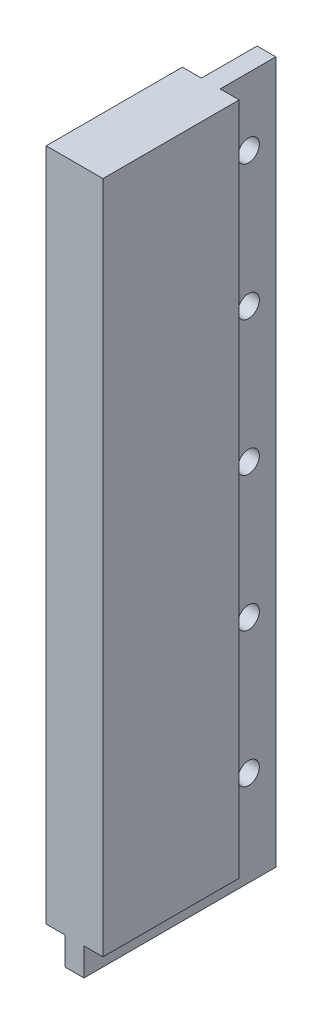
SolidWorks part; units mm, degrees
ref_plane "Front Plane" through (0, 0, 0) normal (1, 0, 0) x (0, 1, 0)
ref_plane "Top Plane" through (0, 0, 0) normal (0, 0, 1) x (0, 1, 0)
ref_plane "Right Plane" through (0, 0, 0) normal (0, 1, 0) x (-1, 0, 0)
sketch "Sketch1" plane through (0, 0, 0) normal (1, 0, 0) x (0, 1, 0)
  line L1 (0, 0) -> (118.75, 0)
  line L2 (0, 0) -> (0, 24)
  line L3 (0, 24) -> (118.75, 24)
  line L4 (118.75, 0) -> (118.75, 24)
  dimension "D1" = 118.75
  dimension "D2" = 24
extrude "Boss-Extrude1" add sketch "Sketch1" against normal blind 10
sketch "Sketch2" plane through (0, 0, 0) normal (0, -1, 0) x (1, 0, 0)
  line L1 (-10, 0) -> (-6.65, 0)
  line L2 (-10, 0) -> (-10, -9.8)
  line L3 (-10, -9.8) -> (-6.65, -9.8)
  line L4 (-6.65, 0) -> (-6.65, -9.8)
  line L5 (0, 0) -> (-3.35, 0)
  line L6 (0, 0) -> (0, -9.8)
  line L7 (0, -9.8) -> (-3.35, -9.8)
  line L8 (-3.35, 0) -> (-3.35, -9.8)
  line L9 (-6.65, -9.8) -> (-3.35, -9.8)
  line L10 (-6.65, -9.8) -> (-6.65, 0)
  line L11 (-6.65, 0) -> (-3.35, 0)
  line L12 (-3.35, -9.8) -> (-3.35, 0)
  line M12 (-10, 0) -> (0, 0)
  dimension "D1" = 9.8
  dimension "D2" = 3.35
  dimension "D3" = 3.35
extrude "Boss-Extrude2" add sketch "Sketch2" against normal through all contours L4 L9 L8 M12
sketch "Sketch3" plane through (0, 0, 0) normal (0, -1, 0) x (1, 0, 0)
  line L0 (-3.35, 20.65) -> (-3.35, 3.35)
  line L1 (0, 24) -> (-10, 24)
  line L2 (0, 24) -> (0, 0)
  line L3 (0, 0) -> (-10, 0)
  line L4 (-10, 24) -> (-10, 0)
  line L5 (-3.35, 3.35) -> (-6.65, 3.35)
  line L6 (-6.65, 20.65) -> (-6.65, 3.35)
  line L7 (-3.35, 20.65) -> (-6.65, 20.65)
  line L9 (-6.65, 20.65) -> (-3.35, 20.65)
  line L10 (-6.65, 20.65) -> (-6.65, 24)
  line L11 (-6.65, 24) -> (-3.35, 24)
  line L12 (-3.35, 20.65) -> (-3.35, 24)
  line L13 (-6.65, 3.35) -> (-3.35, 3.35)
  line L14 (-6.65, 3.35) -> (-6.65, -9.8)
  line L15 (-6.65, -9.8) -> (-3.35, -9.8)
  line L16 (-3.35, 3.35) -> (-3.35, -9.8)
  line M13 (-6.65, 0) -> (-6.65, -9.8)
  line M14 (-6.65, -9.8) -> (-3.35, -9.8)
  line M15 (-3.35, -9.8) -> (-3.35, 0)
  dimension "D1" = 3.35
extrude "Boss-Extrude3" add sketch "Sketch3" along normal blind 4.9 contours L7 L12 L1 L10 | L0 L7 L6 L5 | L16 L5 L14 L3 | L3 M15 M13 M14
sketch "Sketch4" plane through (-6.65, 0, 0) normal (-1, 0, 0) x (0, -1, 0)
  line L1 (-106.875, 0) -> (-118.75, 0)
  line L2 (-106.875, 0) -> (-106.875, -5)
  line L3 (-106.875, -5) -> (-118.75, -5)
  line L4 (-118.75, 0) -> (-118.75, -5)
  circle A0 centre (-106.875, -5) radius 1.9
  dimension "D2" = 3.8
  dimension "D1" = 5
  dimension "D3" = 11.875
extrude "Cut-Extrude1" cut sketch "Sketch4" against normal up to next contours A0
sketch "Sketch5" plane through (0, 118.75, 0) normal (0, 1, 0) x (-1, 0, 0)
  line L0 (3.25, 20.75) -> (3.25, 3.25)
  line L1 (0, 24) -> (10, 24)
  line L2 (0, 24) -> (0, 0)
  line L3 (0, 0) -> (10, 0)
  line L4 (10, 24) -> (10, 0)
  line L5 (3.25, 3.25) -> (6.75, 3.25)
  line L6 (6.75, 20.75) -> (6.75, 3.25)
  line L7 (3.25, 20.75) -> (6.75, 20.75)
  line L9 (3.25, 20.75) -> (6.75, 20.75)
  line L10 (3.25, 20.75) -> (3.25, 24)
  line L11 (3.25, 24) -> (6.75, 24)
  line L12 (6.75, 20.75) -> (6.75, 24)
  dimension "D1" = 3.25
extrude "Cut-Extrude2" [suppressed] cut sketch "Sketch5" against normal blind 5 contours L10 L9 L12 L11 | L0 L5 L6 L7
ref_plane "Plane1" through (0, 59.375, 0) normal (0, -1, 0) x (-1, 0, 0)
mirror "Mirror1" [suppressed] about plane through (0, 59.375, 0) normal (0, -1, 0)
pattern_linear "LPattern1" count 5 spacing 23.75 along (0, -1, 0) of "Cut-Extrude1"
equation "\"whitekey_cutout_length\"= 101.5"
equation "\"key_mount_recess_length\"=50"
equation "\"key_mount_recess_height\"=12.5"
equation "\"key_mount_recess_depth\"=1.5"
equation "\"wall_thickness\"=10"
equation "\"guide_brace_height\"=20"
equation "\"guide_brace_thickness\"=2"
equation "\"dowel_recess_depth\"=10"
equation "\"dowel_recess_offset\"=3.25"
equation "\"base_mount_height\"=40"
equation "\"base_rear_length\"=80"
equation "\"base_front_length\"=111.5"
equation "\"screw_hole_wall_offset\"=7.25"
equation "\"screw_hole_edge_inset\"=\"dowel_recess_depth\"/2"
equation "\"screw_hole_diameter\"=3.8"
equation "\"screw_head_hole_diameter\"=6.7"
equation "\"screw_nut_hole_side_len\"=3.5"
equation "\"screw_shaft_diameter\"=3.5"
equation "\"switch_board_width\"=30"
equation "\"switch_board_wall_offset\"=11.5"
equation "\"heatset_insert_hole_diameter\"=4.8"
equation "\"heatset_insert_hole_depth\"=3.8"
equation "\"D1@Boss-Extrude1\"=\"wall_thickness\""
equation "\"D2@Sketch2\"=\"dowel_recess_offset\"+\"dowel_insert_tolerance\""
equation "\"D3@Sketch2\"=\"dowel_recess_offset\"+\"dowel_insert_tolerance\""
equation "\"D1@Boss-Extrude3\"=\"front_rear_panel_recess_depth\"-\"dowel_insert_tolerance\""
equation "\"D1@Sketch3\"=\"dowel_recess_offset\"+\"dowel_insert_tolerance\""
equation "\"D1@Sketch2\"=\"dowel_recess_depth\"-\"dowel_insert_tolerance\"*2"
equation "\"D1@Sketch4\"=\"screw_hole_edge_inset\""
equation "\"D2@Sketch4\"=\"screw_hole_diameter\""
equation "\"D1@Sketch5\"=\"dowel_recess_offset\""
equation "\"D1@Cut-Extrude2\"=\"front_rear_panel_recess_depth\""
equation "\"screw_nut_recess_offset\"=0.35"
equation "\"screw_head_and_nut_recess_depth\"=2.5"
equation "\"front_rear_panel_width\"=23.75"
equation "\"rod_length_adj\"=0.5"
equation "\"rod_insert_length\"=2.8"
equation "\"D1@Sketch1\"=\"front_rear_panel_width\"*5"
equation "\"switch_board_thickness\"=1.6"
equation "\"front_panel_height\"=24"
equation "\"rod_diameter\"=5"
equation "\"rod_head_diameter\"=8"
equation "\"switch_black_key_mount_height\"=8"
equation "\"switch_white_key_mount_height\"=3"
equation "\"D2@Sketch1\"=\"front_panel_height\""
equation "\"dowel_insert_tolerance\"=0.1"
equation "\"front_rear_panel_recess_depth\"=5"
equation "\"D3@Sketch4\"=\"front_rear_panel_width\"/2"
equation "\"D3@LPattern1\"=\"front_rear_panel_width\""
